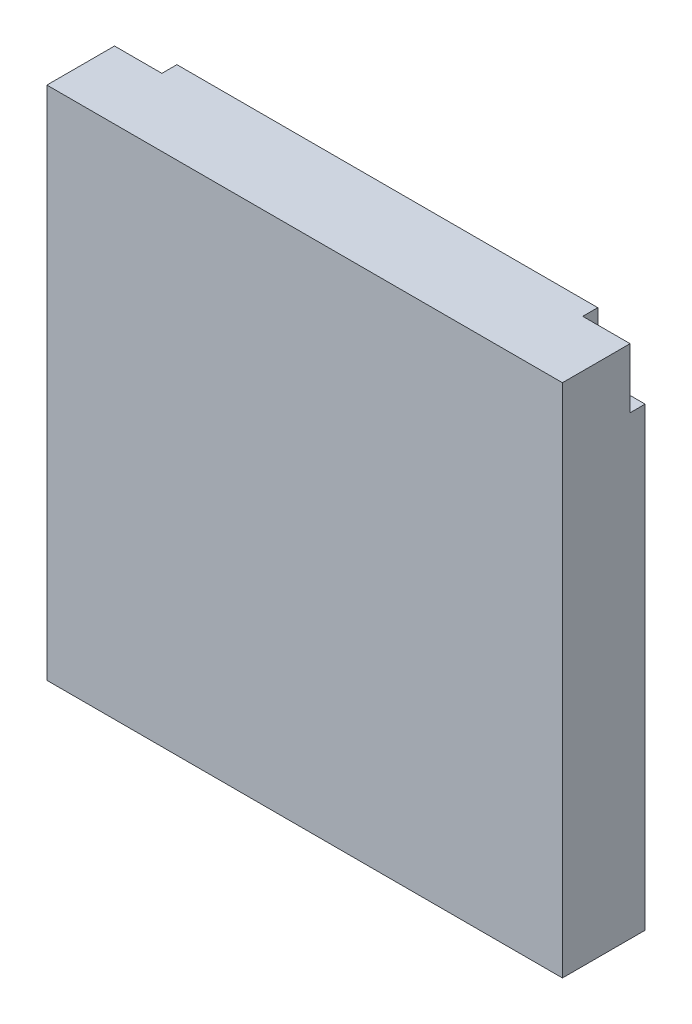
SolidWorks part; units mm, degrees
material "Ceramic Porcelain"
ref_plane "Front Plane" through (0, 0, 0) normal (0, 0, 1) x (1, 0, 0)
ref_plane "Top Plane" through (0, 0, 0) normal (0, 1, 0) x (1, 0, 0)
ref_plane "Right Plane" through (0, 0, 0) normal (1, 0, 0) x (0, 0, -1)
sketch "Sketch1" plane through (0, 0, 0) normal (0, 0, 1) x (1, 0, 0)
  line L1 (0, 0) -> (3.43, 0)
  line L2 (0, 0) -> (0, 3.43)
  line L3 (0, 3.43) -> (3.43, 3.43)
  line L4 (3.43, 0) -> (3.43, 3.43)
  dimension "D1" = 3.43
  dimension "D2" = 3.43
extrude "Boss-Extrude1" add sketch "Sketch1" along normal blind 0.55
sketch "Sketch2" plane through (0, 0, 0) normal (0, 0, -1) x (-1, 0, 0)
  circle A0 centre (-1.715, 1.715) radius 1.28
  dimension "D1" = 2.56
sketch "Sketch3" plane through (0, 0, 0) normal (0, 0, -1) x (-1, 0, 0)
  line L1 (-3.43, 3.43) -> (-3.115, 3.43)
  line L2 (-3.43, 3.43) -> (-3.43, 3.0318)
  line L3 (-3.43, 3.0318) -> (-3.115, 3.0318)
  line L4 (-3.115, 3.43) -> (-3.115, 3.0318)
  line L5 (0, 3.43) -> (-0.315, 3.43)
  line L6 (0, 3.43) -> (0, 3.0318)
  line L7 (0, 3.0318) -> (-0.315, 3.0318)
  line L8 (-0.315, 3.43) -> (-0.315, 3.0318)
  circle A0 centre (-3.115, 0.3289) radius 0.128
extrude "Cut-Extrude1" cut sketch "Sketch3" against normal blind 0.1
